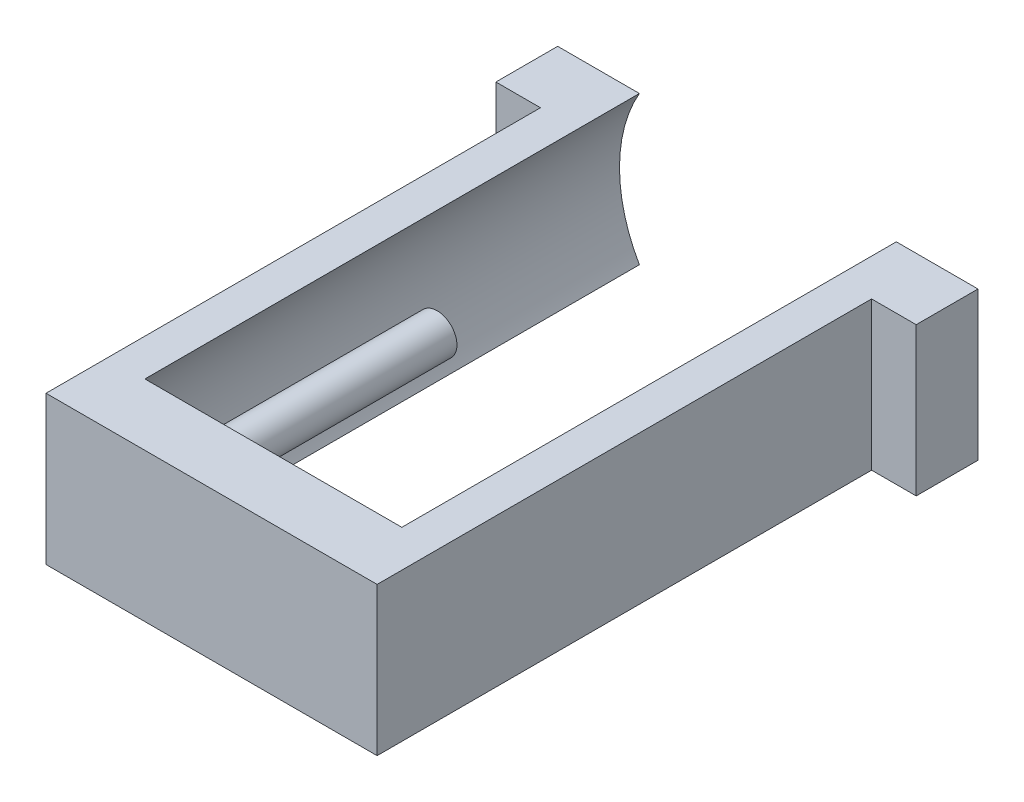
SolidWorks part; units mm, degrees
ref_plane "Plan de face" through (0, 0, 0) normal (0, 0, 1) x (1, 0, 0)
ref_plane "Plan de dessus" through (0, 0, 0) normal (0, 1, 0) x (1, 0, 0)
ref_plane "Plan de droite" through (0, 0, 0) normal (1, 0, 0) x (0, 0, -1)
sketch "Esquisse5" plane through (0, 0, 0) normal (0, 0, 1) x (1, 0, 0)
  line L2 (-17, 6) -> (-17, -6)
  line L3 (-17, -6) -> (-10.3923, -6)
  line L4 (-17, 6) -> (-10.3923, 6)
  line L5 (0, 12) -> (0, -12) construction
  arc A0 (0, 12) -> (0, -12) centre (0, 0) ccw construction
  arc A1 (-10.3923, 6) -> (-10.3923, -6) centre (0, 0) ccw
  dimension "D1" = 24
  dimension "D2" = 6
  dimension "D3" = 6
  dimension "D4" = 17
extrude "Boss.-Extru.2" add sketch "Esquisse5" along normal blind 5
sketch "Esquisse6" plane through (0, 0, 5) normal (0, 0, 1) x (1, 0, 0)
  line L0 (-13.3923, 6) -> (-13.3923, -6)
  line L1 (-10.3923, 6) -> (-17, 6) construction
  line L2 (-17, -6) -> (-10.3923, -6) construction
  line L3 (-13.3923, -6) -> (-10.3923, -6)
  line L4 (-13.3923, 6) -> (-10.3923, 6)
  arc A0 (-10.3923, 6) -> (-10.3923, -6) centre (0, 0) ccw
  dimension "D1" = 3
extrude "Boss.-Extru.3" add sketch "Esquisse6" along normal blind 35
sketch "Esquisse7" plane through (0, 0, 40) normal (0, 0, 1) x (1, 0, 0)
  line L0 (-13.3923, 6) -> (-13.3923, -6)
  line L1 (-13.3923, 6) -> (0, 6)
  line L2 (-13.3923, -6) -> (0, -6)
  line L3 (0, 6) -> (0, -6)
  circle A0 centre (-7.75, 0) radius 1.6
  dimension "D2" = 3.2
  dimension "D1" = 7.75
extrude "Boss.-Extru.4" add sketch "Esquisse7" along normal blind 5
mirror "Symétrie9" about plane through (0, 0, 0) normal (1, 0, 0) of "Boss.-Extru.4"
mirror "Symétrie10" about plane through (0, 0, 0) normal (1, 0, 0) of "Boss.-Extru.3"
mirror "Symétrie11" about plane through (0, 0, 0) normal (1, 0, 0) of "Boss.-Extru.2"
sketch "Esquisse9" plane through (0, 0, 45) normal (0, 0, 1) x (1, 0, 0)
  circle A0 centre (-7.75, 0) radius 1.6
extrude "Boss.-Extru.5" add sketch "Esquisse9" against normal blind 26
mirror "Symétrie12" about plane through (0, 0, 0) normal (1, 0, 0) of "Boss.-Extru.5"
